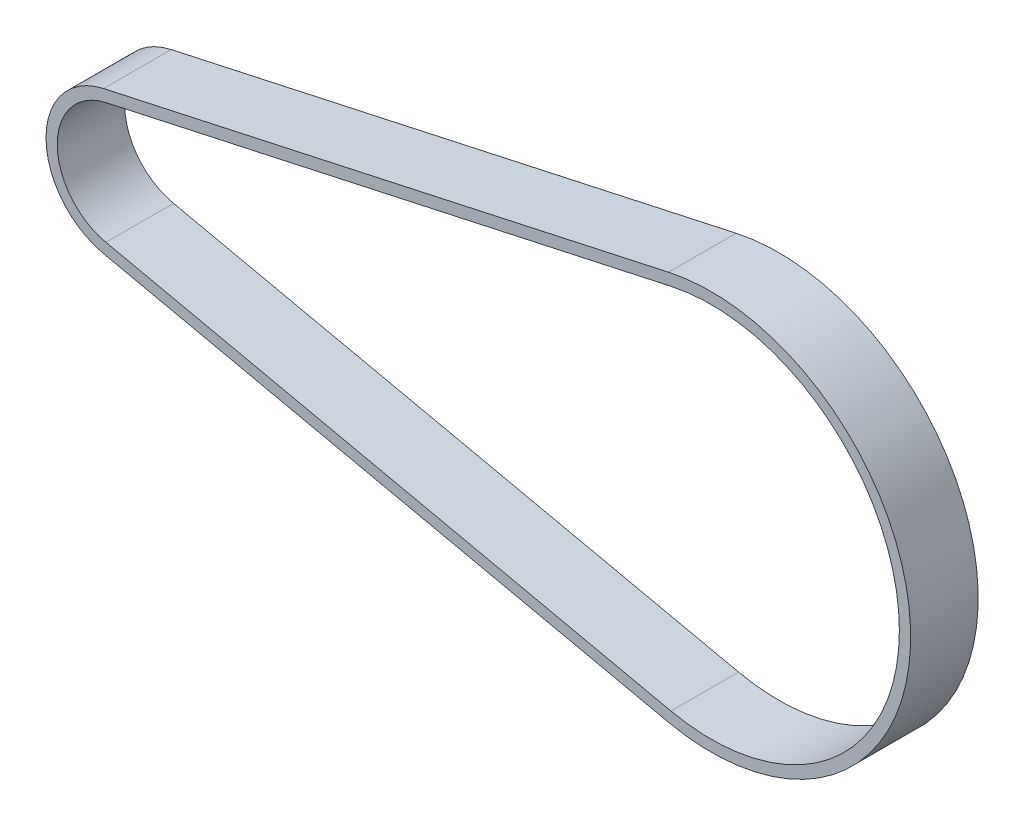
SolidWorks part; units mm, degrees
material "HYPALON"
ref_plane "Alzado" through (0, 0, 0) normal (0, 0, 1) x (1, 0, 0)
ref_plane "Planta" through (0, 0, 0) normal (0, 1, 0) x (1, 0, 0)
ref_plane "Vista lateral" through (0, 0, 0) normal (1, 0, 0) x (0, 0, -1)
sketch "Croquis1" plane through (0, 0, 0) normal (0, 0, 1) x (1, 0, 0)
  line L0 (-1.1738, 5.3733) -> (49.0068, 16.3348)
  line L1 (-1.1738, -5.3733) -> (49.0068, -16.3348)
  line L2 (-1.3872, 6.3503) -> (48.7934, 17.3118)
  line L3 (-1.3872, -6.3503) -> (48.7934, -17.3118)
  arc A0 (-1.1738, 5.3733) -> (-1.1738, -5.3733) centre (0, 0) ccw
  arc A1 (49.0068, -16.3348) -> (49.0068, 16.3348) centre (52.575, 0) ccw
  arc A2 (48.7934, -17.3118) -> (48.7934, 17.3118) centre (52.575, 0) ccw
  arc A3 (-1.3872, 6.3503) -> (-1.3872, -6.3503) centre (0, 0) ccw
  dimension "D1" = 11
  dimension "D2" = 33.44
  dimension "D3" = 52.575
  dimension "D4" = 1
extrude "Saliente-Extruir1" add sketch "Croquis1" along normal blind 6
